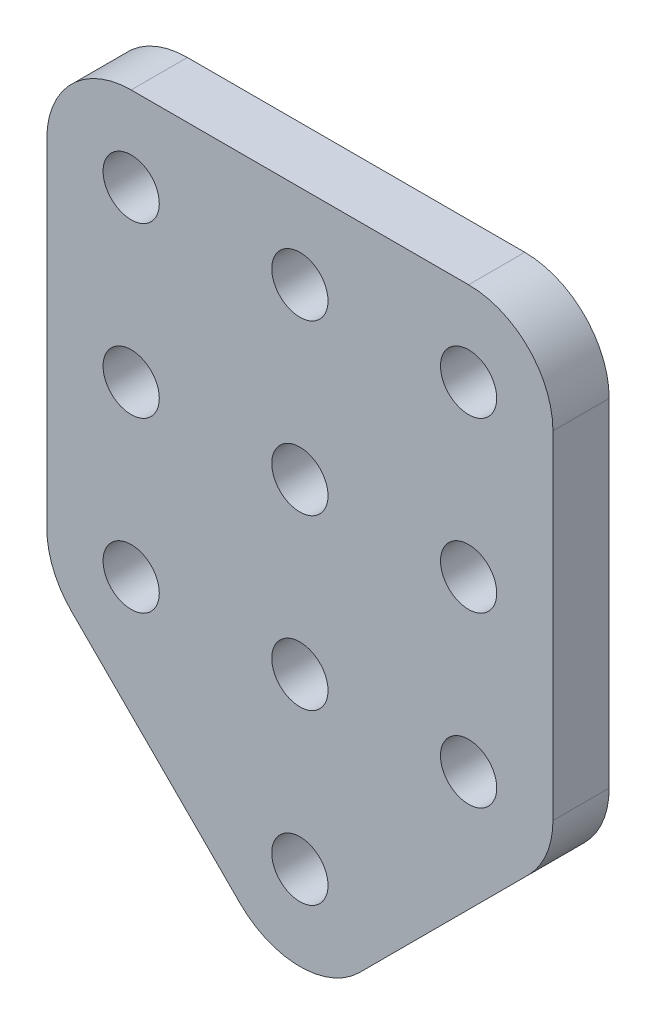
SolidWorks part; units mm, degrees
ref_plane "Alzado" through (0, 0, 0) normal (0, 0, 1) x (1, 0, 0)
ref_plane "Planta" through (0, 0, 0) normal (0, 1, 0) x (1, 0, 0)
ref_plane "Vista lateral" through (0, 0, 0) normal (1, 0, 0) x (0, 0, -1)
sketch "Model" plane through (0, 0, 0) normal (0, 0, 1) x (1, 0, 0)
  line L0 (174.2271, 213.1787) -> (174.2271, 204.1787)
  line L1 (196.7271, 226.6787) -> (178.7271, 226.6787)
  line L2 (174.2271, 213.1787) -> (174.2271, 222.1787)
  line L3 (201.2271, 222.1787) -> (201.2271, 204.1787)
  line L4 (190.909, 191.9967) -> (199.909, 200.9967)
  line L5 (184.5451, 191.9967) -> (175.5451, 200.9967)
  circle A0 centre (187.7271, 204.1787) radius 1.5
  circle A1 centre (178.7271, 204.1787) radius 1.5
  circle A2 centre (187.7271, 213.1787) radius 1.5
  circle A3 centre (178.7271, 213.1787) radius 1.5
  circle A4 centre (196.7271, 213.1787) radius 1.5
  circle A5 centre (187.7271, 195.1787) radius 1.5
  circle A6 centre (196.7271, 204.1787) radius 1.5
  arc A7 (184.5451, 191.9967) -> (190.909, 191.9967) centre (187.7271, 195.1787) ccw
  arc A8 (199.909, 200.9967) -> (201.2271, 204.1787) centre (196.7271, 204.1787) ccw
  arc A9 (174.2271, 204.1787) -> (175.5451, 200.9967) centre (178.7271, 204.1787) ccw
  circle A10 centre (187.7271, 222.1787) radius 1.5
  circle A11 centre (178.7271, 222.1787) radius 1.5
  circle A12 centre (196.7271, 222.1787) radius 1.5
  arc A13 (201.2271, 222.1787) -> (196.7271, 226.6787) centre (196.7271, 222.1787) ccw
  arc A14 (178.7271, 226.6787) -> (174.2271, 222.1787) centre (178.7271, 222.1787) ccw
extrude "Saliente-Extruir1" add sketch "Model" along normal blind 3
